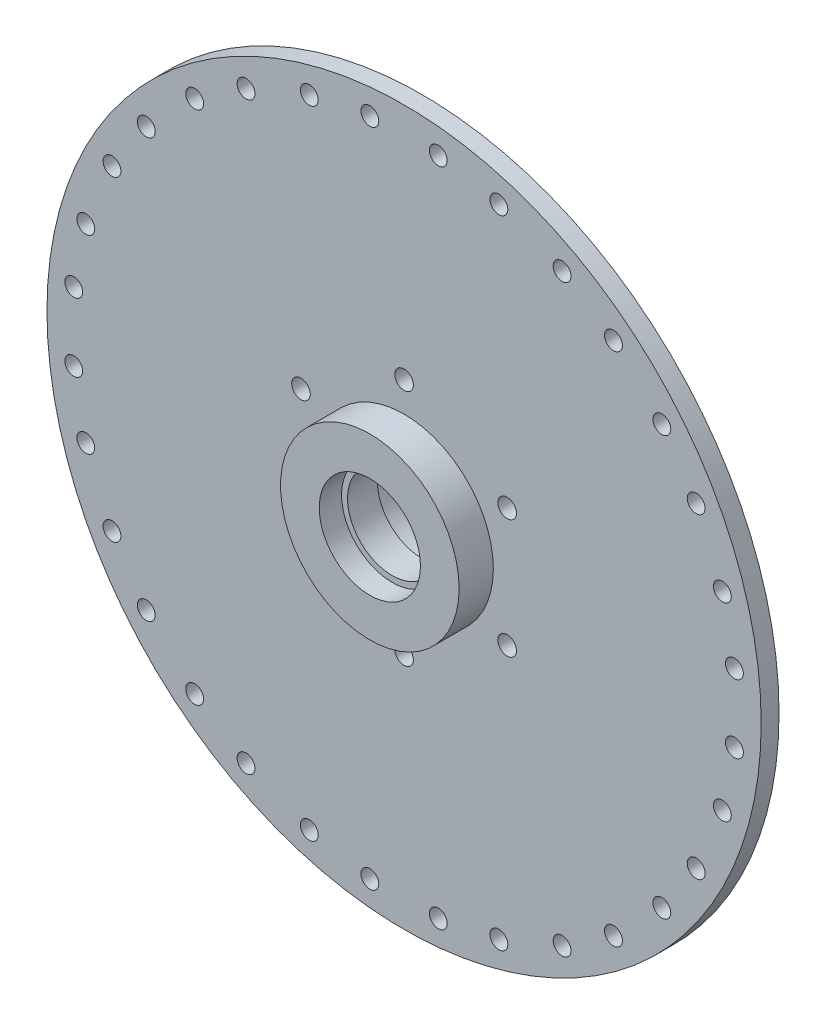
SolidWorks part; units mm, degrees
ref_plane "Piano frontale" through (0, 0, 0) normal (0, 0, 1) x (1, 0, 0)
ref_plane "Piano superiore" through (0, 0, 0) normal (0, 1, 0) x (1, 0, 0)
ref_plane "Piano destro" through (0, 0, 0) normal (1, 0, 0) x (0, 0, -1)
sketch "Schizzo1" plane through (0, 0, 0) normal (0, 0, 1) x (1, 0, 0)
  line L0 (0, 317.5795) -> (0, -73.3653) construction
  line L5 (-324.2951, 0) -> (324.2951, 0) construction
  line L17 (0, -324.2951) -> (0, 324.2951) construction
  circle A0 centre (0, 0) radius 240
  circle A34 centre (0, 0) radius 80 construction
  circle A35 centre (0, 80) radius 6.25
  circle A36 centre (69.282, 40) radius 6.25
  circle A37 centre (69.282, -40) radius 6.25
  circle A38 centre (0, -80) radius 6.25
  circle A39 centre (-69.282, -40) radius 6.25
  circle A40 centre (-69.282, 40) radius 6.25
  dimension "D12" = 6
extrude "Estrusione-Estrusione1" add sketch "Schizzo1" along normal blind 12
sketch "Schizzo2" plane through (0, 0, 12) normal (0, 0, 1) x (1, 0, 0)
  circle A0 centre (0, 0) radius 60
  dimension "D1" = 120
extrude "Estrusione-Estrusione2" add sketch "Schizzo2" along normal blind 23 contours A0
sketch "Schizzo3" plane through (0, 0, 0) normal (0, 0, -1) x (-1, 0, 0)
  circle A0 centre (0, 0) radius 67.5
  dimension "D1" = 135
extrude "Estrusione-Estrusione3" add sketch "Schizzo3" along normal blind 15 contours A0
sketch "Schizzo4" plane through (0, 0, 35) normal (0, 0, 1) x (1, 0, 0)
  circle A0 centre (0, 0) radius 34
  dimension "D1" = 68
extrude "Taglio-Estrusione1" cut sketch "Schizzo4" against normal blind 15
sketch "Schizzo5" plane through (0, 0, 20) normal (0, 0, 1) x (1, 0, 0)
  circle A0 centre (0, 0) radius 30
  dimension "D1" = 60
extrude "Taglio-Estrusione2" cut sketch "Schizzo5" against normal blind 20 contours A0
sketch "Schizzo6" plane through (0, 0, -15) normal (0, 0, -1) x (-1, 0, 0)
  circle A0 centre (0, 0) radius 34
  dimension "D1" = 68
extrude "Taglio-Estrusione3" cut sketch "Schizzo6" against normal blind 15 contours A0
sketch "Schizzo7" plane through (0, 0, 12) normal (0, 0, 1) x (1, 0, 0)
  line L0 (0, 0) -> (-222, 0) construction
  line L1 (-222, 0) -> (-222, 23) construction
  line L2 (-222, 0) -> (-222, -23) construction
  circle A0 centre (-222, 23) radius 6
  circle A1 centre (-222, -23) radius 6
  dimension "D1" = 46
  dimension "D2" = 12
  dimension "D3" = 12
  dimension "D4" = 222
extrude "Taglio-Estrusione4" cut sketch "Schizzo7" against normal up to surface (12 mm away) up to face at (67.5, 0, 0)
pattern_circular "RipetizioneCircolare1" count 16 over 360 about axis through (0, 0, 0) along (0, 0, 1) of "Taglio-Estrusione4"
